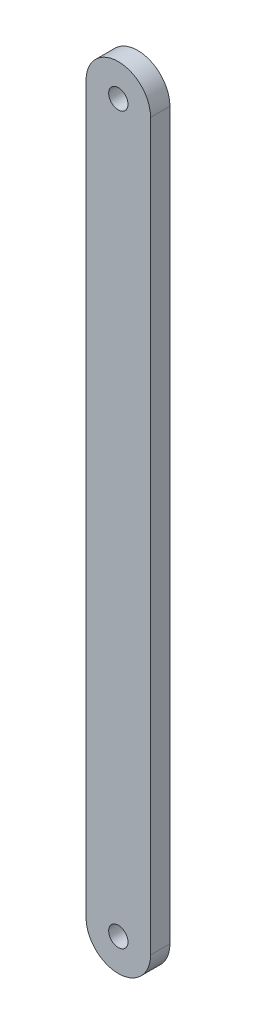
SolidWorks part; units mm, degrees
ref_plane "Front Plane" through (0, 0, 0) normal (0, 0, 1) x (1, 0, 0)
ref_plane "Top Plane" through (0, 0, 0) normal (0, 1, 0) x (1, 0, 0)
ref_plane "Right Plane" through (0, 0, 0) normal (1, 0, 0) x (0, 0, -1)
sketch "Sketch1" plane through (0, 0, 0) normal (0, 0, 1) x (1, 0, 0)
  line L0 (0, 0) -> (0, 225) construction
  line L1 (-10, 0) -> (-10, 225)
  line L2 (10, 0) -> (10, 225)
  arc A0 (-10, 0) -> (10, 0) centre (0, 0) ccw
  arc A1 (10, 225) -> (-10, 225) centre (0, 225) ccw
  point P3 (0, 112.5)
  dimension "D1" = 10
  dimension "D2" = 225
extrude "Boss-Extrude1" add sketch "Sketch1" along normal blind 6
sketch "Sketch2" plane through (0, 0, 6) normal (0, 0, 1) x (1, 0, 0)
  circle A0 centre (0, 225) radius 3
  circle A1 centre (0, 0) radius 3
  dimension "D1" = 6
extrude "Cut-Extrude1" cut sketch "Sketch2" against normal through all
